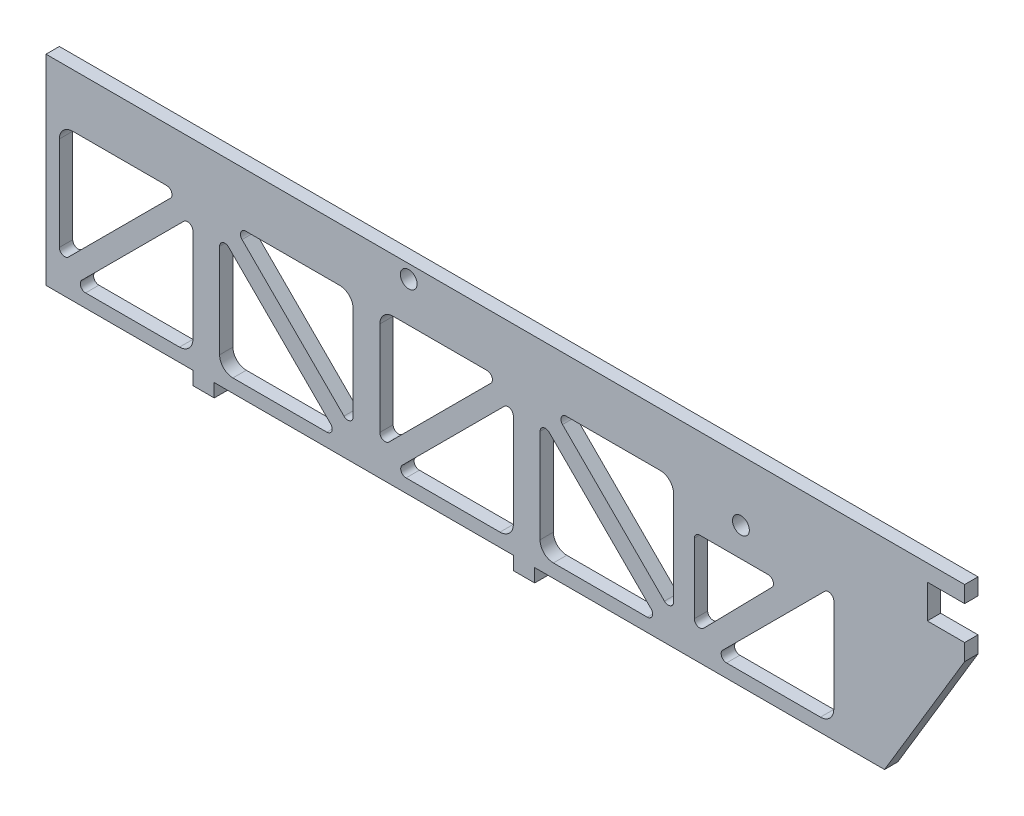
SolidWorks part; units mm, degrees
material "Pine"
ref_plane "Front Plane" through (0, 0, 0) normal (0, 0, 1) x (1, 0, 0)
ref_plane "Top Plane" through (0, 0, 0) normal (0, 1, 0) x (1, 0, 0)
ref_plane "Right Plane" through (0, 0, 0) normal (1, 0, 0) x (0, 0, -1)
sketch "Model" plane through (0, 0, 0) normal (0, 0, 1) x (1, 0, 0)
  line L0 (312.6855, 15.1239) -> (345.2281, 48.2988)
  line L1 (343.4149, 52.6175) -> (310.8722, 52.6175)
  line L2 (308.3322, 50.0775) -> (308.3322, 16.9026)
  line L8 (171.2321, 6.35) -> (215.9, 6.35)
  line L9 (217.9139, 59.1639) -> (169.4361, 10.6861)
  line L10 (222.25, 57.3679) -> (222.25, 12.7)
  line L11 (234.95, 57.3679) -> (234.95, 12.7)
  line L12 (239.2861, 59.1639) -> (287.7639, 10.6861)
  line L13 (241.3, 6.35) -> (285.9679, 6.35)
  line L14 (294.1139, 17.0361) -> (245.6361, 65.5139)
  line L15 (247.4321, 69.85) -> (292.1, 69.85)
  line L16 (298.45, 63.5) -> (298.45, 18.8321)
  line L17 (323.6321, 6.35) -> (368.3, 6.35)
  line L18 (370.3139, 59.1639) -> (321.8361, 10.6861)
  line L19 (374.65, 57.3679) -> (374.65, 12.7)
  line L20 (18.8321, 6.35) -> (63.5, 6.35)
  line L21 (17.0361, 10.6861) -> (65.5139, 59.1639)
  line L22 (69.85, 57.3679) -> (69.85, 12.7)
  line L23 (82.55, 57.3679) -> (82.55, 12.7)
  line L24 (86.8861, 59.1639) -> (135.3639, 10.6861)
  line L25 (88.9, 6.35) -> (133.5679, 6.35)
  line L26 (93.2361, 65.5139) -> (141.7139, 17.0361)
  line L27 (95.0321, 69.85) -> (139.7, 69.85)
  line L28 (146.05, 63.5) -> (146.05, 18.8321)
  line L29 (163.0861, 17.0361) -> (211.5639, 65.5139)
  line L30 (158.75, 63.5) -> (158.75, 18.8321)
  line L31 (165.1, 69.85) -> (209.7679, 69.85)
  line L35 (419.1, 87.376) -> (419.1, 71.374)
  line L36 (436.88, 87.376) -> (419.1, 87.376)
  line L37 (436.88, 87.376) -> (436.88, 95.25)
  line L38 (0, 95.25) -> (436.88, 95.25)
  line L39 (0, 0) -> (0, 95.25)
  line L40 (0, 0) -> (398.78, 0)
  line L41 (436.88, 63.5) -> (398.78, 0)
  line L42 (436.88, 63.5) -> (436.88, 71.374)
  line L43 (419.1, 71.374) -> (436.88, 71.374)
  line L44 (6.35, 63.5) -> (6.35, 18.8321)
  line L45 (12.7, 69.85) -> (57.3679, 69.85)
  line L46 (59.1639, 65.5139) -> (10.6861, 17.0361)
  arc A0 (215.9, 6.35) -> (222.25, 12.7) centre (215.9, 12.7) ccw
  arc A1 (169.4361, 10.6861) -> (171.2321, 6.35) centre (171.2321, 8.89) ccw
  arc A2 (222.25, 57.3679) -> (217.9139, 59.1639) centre (219.71, 57.3679) ccw
  arc A3 (239.2861, 59.1639) -> (234.95, 57.3679) centre (237.49, 57.3679) ccw
  arc A4 (285.9679, 6.35) -> (287.7639, 10.6861) centre (285.9679, 8.89) ccw
  arc A5 (234.95, 12.7) -> (241.3, 6.35) centre (241.3, 12.7) ccw
  arc A6 (247.4321, 69.85) -> (245.6361, 65.5139) centre (247.4321, 67.31) ccw
  arc A7 (298.45, 63.5) -> (292.1, 69.85) centre (292.1, 63.5) ccw
  arc A8 (294.1139, 17.0361) -> (298.45, 18.8321) centre (295.91, 18.8321) ccw
  arc A9 (321.8361, 10.6861) -> (323.6321, 6.35) centre (323.6321, 8.89) ccw
  arc A10 (374.65, 57.3679) -> (370.3139, 59.1639) centre (372.11, 57.3679) ccw
  arc A11 (368.3, 6.35) -> (374.65, 12.7) centre (368.3, 12.7) ccw
  arc A12 (63.5, 6.35) -> (69.85, 12.7) centre (63.5, 12.7) ccw
  arc A13 (17.0361, 10.6861) -> (18.8321, 6.35) centre (18.8321, 8.89) ccw
  arc A14 (69.85, 57.3679) -> (65.5139, 59.1639) centre (67.31, 57.3679) ccw
  arc A15 (86.8861, 59.1639) -> (82.55, 57.3679) centre (85.09, 57.3679) ccw
  arc A16 (133.5679, 6.35) -> (135.3639, 10.6861) centre (133.5679, 8.89) ccw
  arc A17 (82.55, 12.7) -> (88.9, 6.35) centre (88.9, 12.7) ccw
  arc A18 (95.0321, 69.85) -> (93.2361, 65.5139) centre (95.0321, 67.31) ccw
  arc A19 (146.05, 63.5) -> (139.7, 69.85) centre (139.7, 63.5) ccw
  arc A20 (141.7139, 17.0361) -> (146.05, 18.8321) centre (143.51, 18.8321) ccw
  arc A21 (158.75, 18.8321) -> (163.0861, 17.0361) centre (161.29, 18.8321) ccw
  arc A22 (165.1, 69.85) -> (158.75, 63.5) centre (165.1, 63.5) ccw
  arc A23 (211.5639, 65.5139) -> (209.7679, 69.85) centre (209.7679, 67.31) ccw
  arc A24 (345.2281, 48.2988) -> (343.4149, 52.6175) centre (343.4149, 50.0775) ccw
  arc A25 (310.8722, 52.6175) -> (308.3322, 50.0775) centre (310.8722, 50.0775) ccw
  arc A26 (312.6855, 15.1239) -> (308.3322, 16.9026) centre (310.8722, 16.9026) cw
  arc A27 (6.35, 18.8321) -> (10.6861, 17.0361) centre (8.89, 18.8321) ccw
  arc A28 (12.7, 69.85) -> (6.35, 63.5) centre (12.7, 63.5) ccw
  arc A29 (59.1639, 65.5139) -> (57.3679, 69.85) centre (57.3679, 67.31) ccw
  circle A30 centre (172.4917, 88.8013) radius 4
  circle A31 centre (330.4797, 66.4493) radius 4
  dimension "D2" = 6.4487
  dimension "D3" = 172.4917
  dimension "D4" = 8
  dimension "D5" = 22.352
  dimension "D6" = 8
  dimension "D8" = 2.54
  dimension "D1" = 95.25
  dimension "D7" = 157.988
extrude "Boss-Extrude2" add sketch "Model" along normal blind 6.35
sketch "Sketch1" plane through (0, 0, 6.35) normal (0, 0, 1) x (1, 0, 0)
  line L0 (69.85, 12.7) -> (69.85, 0) construction
  line L1 (146.05, 18.8321) -> (146.05, 0) construction
  line L2 (146.05, 18.8321) -> (146.05, 63.5) construction
  line L3 (0, 0) -> (398.78, 0) construction
  line L4 (222.25, 12.7) -> (222.25, 0) construction
  line L5 (222.25, 12.7) -> (222.25, 57.3679) construction
  line L8 (69.85, 0) -> (80.01, 0)
  line L9 (69.85, 0) -> (69.85, -6.35)
  line L10 (69.85, -6.35) -> (80.01, -6.35)
  line L11 (80.01, 0) -> (80.01, -6.35)
  line L16 (222.25, 0) -> (232.41, 0)
  line L17 (222.25, 0) -> (222.25, -6.35)
  line L18 (222.25, -6.35) -> (232.41, -6.35)
  line L19 (232.41, 0) -> (232.41, -6.35)
  point P11 (69.85, -6.8621)
  dimension "D1" = 10.16
  dimension "D2" = 6.35
  dimension "D3" = 10.16
  dimension "D4" = 6.35
extrude "Boss-Extrude3" add sketch "Sketch1" against normal up to surface (6.35 mm away) up to face at (321.5295, 39.2174, 0)
